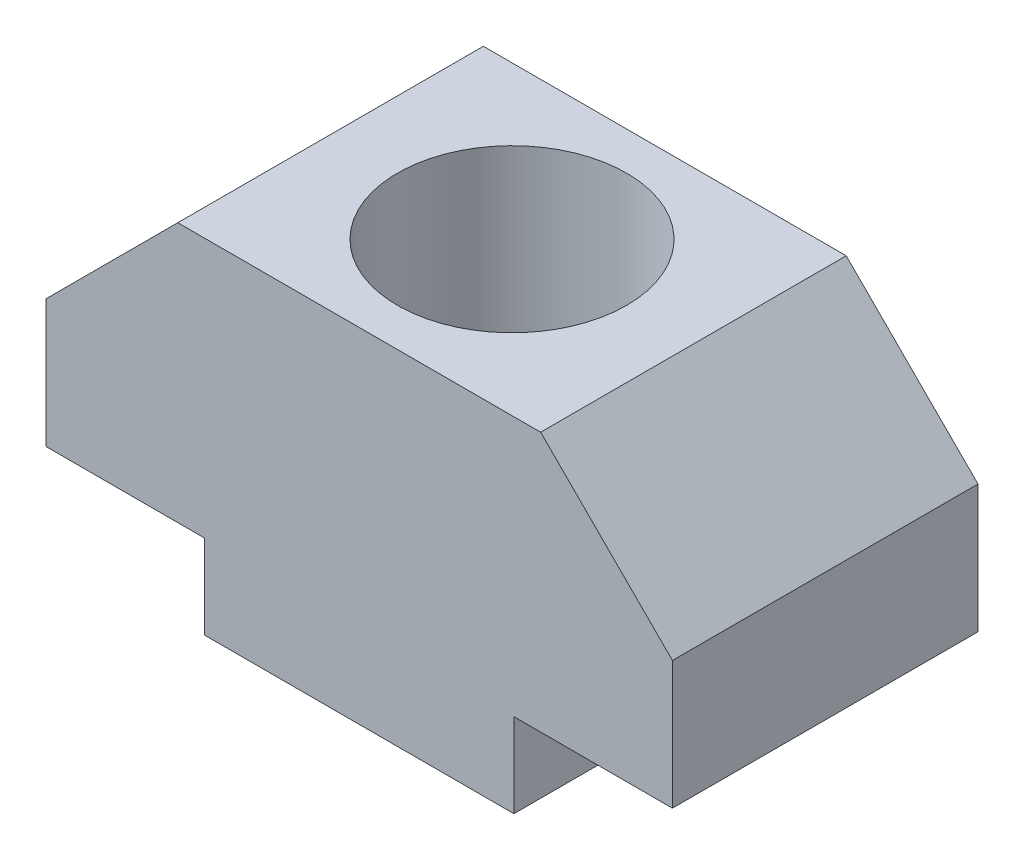
SolidWorks part; units mm, degrees
ref_plane "Front Plane" through (0, 0, 0) normal (0, 0, 1) x (1, 0, 0)
ref_plane "Top Plane" through (0, 0, 0) normal (0, 1, 0) x (1, 0, 0)
ref_plane "Right Plane" through (0, 0, 0) normal (1, 0, 0) x (0, 0, -1)
sketch "Sketch1" plane through (0, 0, 0) normal (0, 0, 1) x (1, 0, 0)
  line L0 (-4.05, 0) -> (4.05, 0)
  line L1 (0, 9.6092) -> (0, -1.1506) construction
  line L2 (4.05, 0) -> (4.05, 2.2)
  line L3 (4.05, 2.2) -> (8.2, 2.2)
  line L4 (8.2, 2.2) -> (8.2, 5.55)
  line L5 (8.2, 5.55) -> (4.75, 9)
  line L6 (4.75, 9) -> (-4.75, 9)
  line L8 (-4.75, 9) -> (-8.2, 5.55)
  line L9 (-8.2, 5.55) -> (-8.2, 2.2)
  line L10 (-8.2, 2.2) -> (-4.05, 2.2)
  line L11 (-4.05, 2.2) -> (-4.05, 0)
  dimension "D1" = 2.2
  dimension "D2" = 8.1
  dimension "D3" = 9
  dimension "D4" = 16.4
  dimension "D5" = 135
  dimension "D6" = 9.5
extrude "Extrude1" add sketch "Sketch1" along normal mid plane 8
sketch "Sketch2" plane through (0, 0, 0) normal (0, 1, 0) x (1, 0, 0)
  circle A0 centre (0, 0) radius 3
  dimension "D1" = 6
extrude "Cut-Extrude1" cut sketch "Sketch2" along normal up to next
cosmetic thread "Cosmetic Thread1" parameters "D2"=6.001
